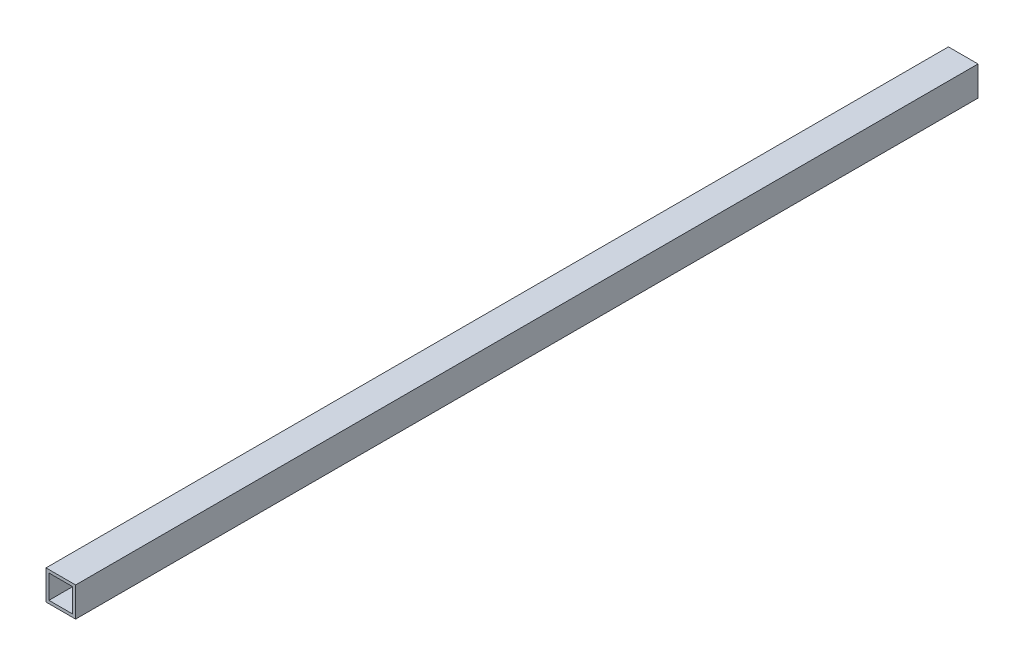
SolidWorks part; units mm, degrees
ref_plane "Front Plane" through (0, 0, 0) normal (0, 0, 1) x (1, 0, 0)
ref_plane "Top Plane" through (0, 0, 0) normal (0, 1, 0) x (1, 0, 0)
ref_plane "Right Plane" through (0, 0, 0) normal (1, 0, 0) x (0, 0, -1)
sketch "Sketch1" plane through (0, 0, 0) normal (0, 0, 1) x (1, 0, 0)
  line L0 (-8, -8) -> (-8, 8)
  line L1 (10, -10) -> (-10, -10)
  line L2 (10, -10) -> (10, 10)
  line L3 (10, 10) -> (-10, 10)
  line L4 (-10, -10) -> (-10, 10)
  line L5 (10, -10) -> (-10, 10) construction
  line L6 (10, 10) -> (-10, -10) construction
  line L7 (8, 8) -> (-8, 8)
  line L8 (8, -8) -> (8, 8)
  line L9 (8, -8) -> (-8, -8)
  point P0 (0, 0)
  dimension "Width" = 20
  dimension "Wall thk." = 2
sketch "Sketch2" plane through (0, 0, 0) normal (1, 0, 0) x (0, 0, -1)
  line L0 (-304.8, 0) -> (304.8, 0) construction
  point P0 (-292.608, 0)
  point P3 (292.608, 0)
  point P4 (0, 0)
  dimension "Length" = 609.6
  dimension "D1" = 12.192
  dimension "D2" = 12.192
sketch "Sketch3" plane through (0, 0, 0) normal (0, 0, 1) x (1, 0, 0)
  line L0 (8, -8) -> (-8, -8) construction
  line L1 (8, -8) -> (8, 8) construction
  line L2 (8, 8) -> (-8, 8) construction
  line L3 (-8, -8) -> (-8, 8) construction
  line L4 (10, -10) -> (-10, -10) construction
  line L5 (10, -10) -> (10, 10) construction
  line L6 (10, 10) -> (-10, 10) construction
  line L7 (-10, -10) -> (-10, 10) construction
  line L8 (8, -8) -> (-8, -8)
  line L9 (8, -8) -> (8, 8)
  line L10 (8, 8) -> (-8, 8)
  line L11 (-8, -8) -> (-8, 8)
  line L12 (10, -10) -> (-10, -10)
  line L13 (10, -10) -> (10, 10)
  line L14 (10, 10) -> (-10, 10)
  line L15 (-10, -10) -> (-10, 10)
extrude "Boss-Extrude1" add sketch "Sketch3" along normal up to vertex (304.8 mm away) and the other way up to vertex (304.8 mm away) up to point (0, 0, 304.8) other way up to point (0, 0, -304.8)
equation "\"D1@Sketch2\"=\"Length@Sketch2\"*.02"
equation "\"D2@Sketch2\"=\"D1@Sketch2\""
